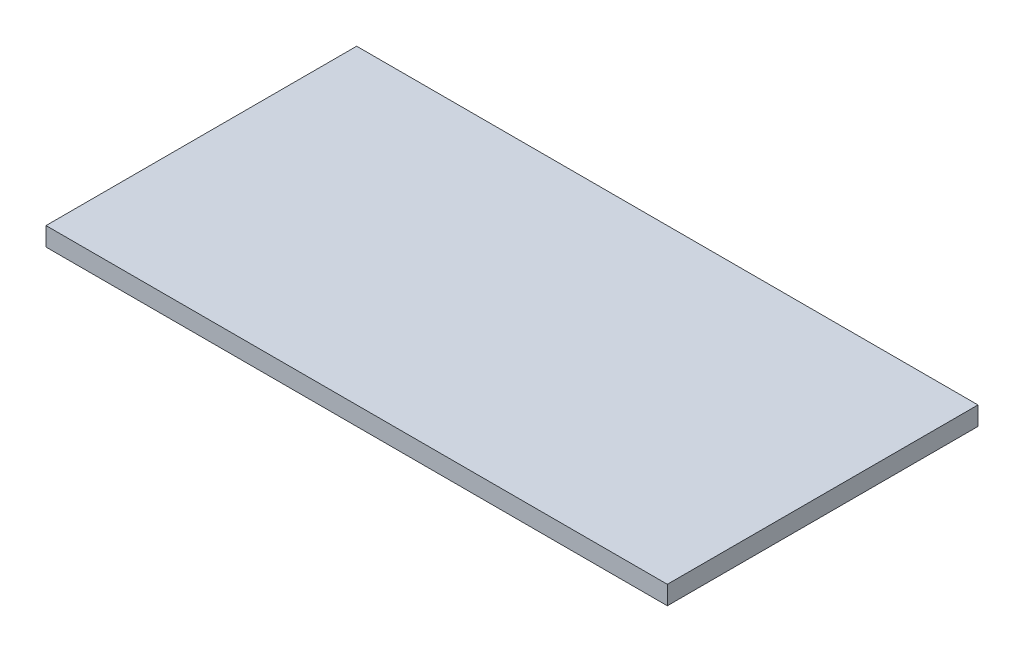
SolidWorks part; units mm, degrees
material "A-玻璃纤维"
ref_plane "前视基准面" through (0, 0, 0) normal (0, 0, 1) x (1, 0, 0)
ref_plane "上视基准面" through (0, 0, 0) normal (0, 1, 0) x (1, 0, 0)
ref_plane "右视基准面" through (0, 0, 0) normal (1, 0, 0) x (0, 0, -1)
sketch "草图1" plane through (0, 0, 0) normal (0, 1, 0) x (1, 0, 0)
  line L1 (-50, 25) -> (50, 25)
  line L2 (-50, 25) -> (-50, -25)
  line L3 (-50, -25) -> (50, -25)
  line L4 (50, 25) -> (50, -25)
  line L5 (-50, 25) -> (50, -25) construction
  line L6 (-50, -25) -> (50, 25) construction
  point P0 (0, 0)
  dimension "D1" = 100
  dimension "D2" = 50
extrude "凸台-拉伸1" add sketch "草图1" along normal blind 3
